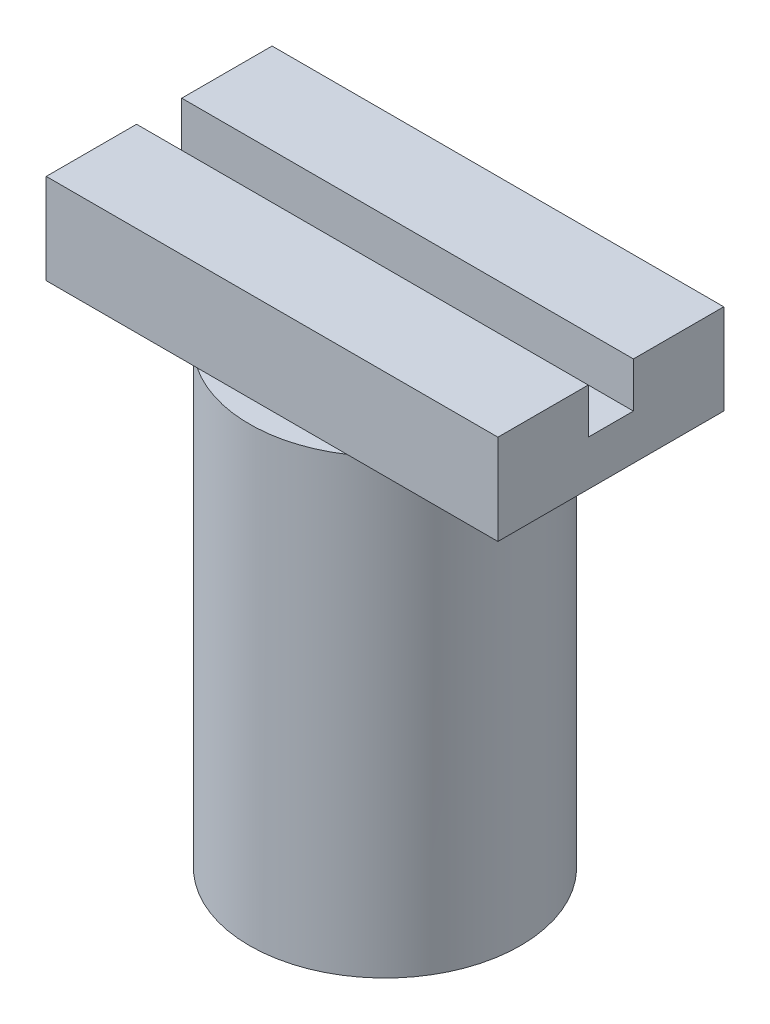
SolidWorks part; units mm, degrees
ref_plane "Front Plane" through (0, 0, 0) normal (0, 0, 1) x (1, 0, 0)
ref_plane "Top Plane" through (0, 0, 0) normal (0, 1, 0) x (1, 0, 0)
ref_plane "Right Plane" through (0, 0, 0) normal (1, 0, 0) x (0, 0, -1)
sketch "Sketch1" plane through (0, 0, 0) normal (0, 1, 0) x (1, 0, 0)
  circle A0 centre (0, 0) radius 3
  dimension "D1" = 6
extrude "Boss-Extrude1" add sketch "Sketch1" along normal blind 10
sketch "Sketch2" plane through (0, 10, 0) normal (0, 1, 0) x (1, 0, 0)
  line L1 (-5, -2.5) -> (5, -2.5)
  line L2 (-5, -2.5) -> (-5, 2.5)
  line L3 (-5, 2.5) -> (5, 2.5)
  line L4 (5, -2.5) -> (5, 2.5)
  line L5 (-5, -2.5) -> (5, 2.5) construction
  line L6 (-5, 2.5) -> (5, -2.5) construction
  point P0 (0, 0)
  dimension "D1" = 10
  dimension "D2" = 5
extrude "Boss-Extrude2" add sketch "Sketch2" along normal blind 2
sketch "Sketch3" plane through (0, 12, 0) normal (0, 1, 0) x (1, 0, 0)
  line L0 (-5, 2.5) -> (-5, -2.5) construction
  line L1 (5, 0.5) -> (-5, 0.5)
  line L2 (5, 0.5) -> (5, -0.5)
  line L3 (5, -0.5) -> (-5, -0.5)
  line L4 (-5, 0.5) -> (-5, -0.5)
  line L5 (5, 0.5) -> (-5, -0.5) construction
  line L6 (5, -0.5) -> (-5, 0.5) construction
  point P0 (0, 0)
  dimension "D1" = 1
extrude "Cut-Extrude1" cut sketch "Sketch3" against normal blind 1
